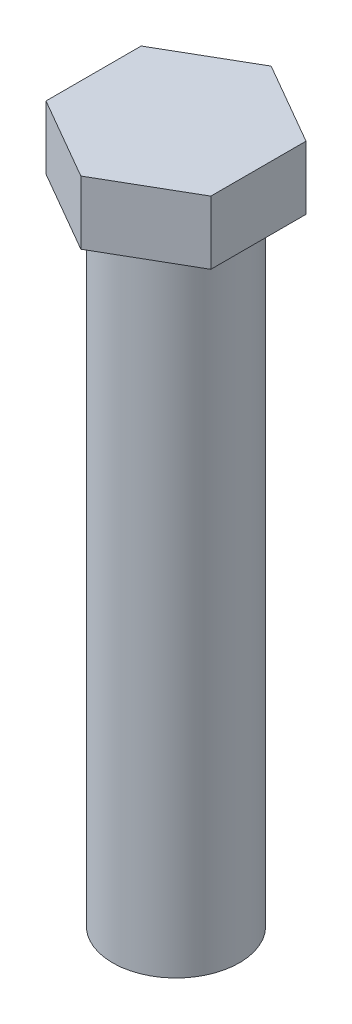
SolidWorks part; units mm, degrees
material "Сталь 45 ГОСТ 1050-88"
ref_plane "Front Plane" through (0, 0, 0) normal (0, 0, 1) x (1, 0, 0)
ref_plane "Top Plane" through (0, 0, 0) normal (0, 1, 0) x (1, 0, 0)
ref_plane "Right Plane" through (0, 0, 0) normal (1, 0, 0) x (0, 0, -1)
sketch "Sketch2" plane through (0, 0, 0) normal (0, 0, 1) x (1, 0, 0)
  line L0 (0, 59.5238) -> (0, -37.619) construction
  line L1 (5, 25) -> (0, 25) construction
  line L2 (0, -25) -> (-5, -25)
  line L3 (5, -25) -> (5, 25) construction
  line L4 (0, 25) -> (-5, 25)
  line L5 (-5, -25) -> (-5, 25)
  line L6 (0, 0) -> (-5, 25) construction
  line L7 (0, 0) -> (-5, -25) construction
  line L8 (5, 25) -> (0, 0) construction
  line L9 (5, -25) -> (0, 0) construction
  line L10 (5, -25) -> (0, -25) construction
  line L11 (0, 25) -> (0, -25)
  point P3 (0, 0)
  dimension "D1" = 10
  dimension "D2" = 50
revolve "Revolve1" add sketch "Sketch2" angle 360 about L0
sketch "Sketch3" plane through (0, 25, 0) normal (0, 1, 0) x (1, 0, 0)
  line L1 (-6.5, 3.7528) -> (-6.5, -3.7528)
  line L2 (-6.5, -3.7528) -> (0, -7.5056)
  line L3 (0, -7.5056) -> (6.5, -3.7528)
  line L4 (6.5, -3.7528) -> (6.5, 3.7528)
  line L5 (6.5, 3.7528) -> (0, 7.5056)
  line L6 (0, 7.5056) -> (-6.5, 3.7528)
  circle A0 centre (0, 0) radius 6.5 construction
  dimension "D1" = 13
extrude "Boss-Extrude1" add sketch "Sketch3" along normal blind 5
